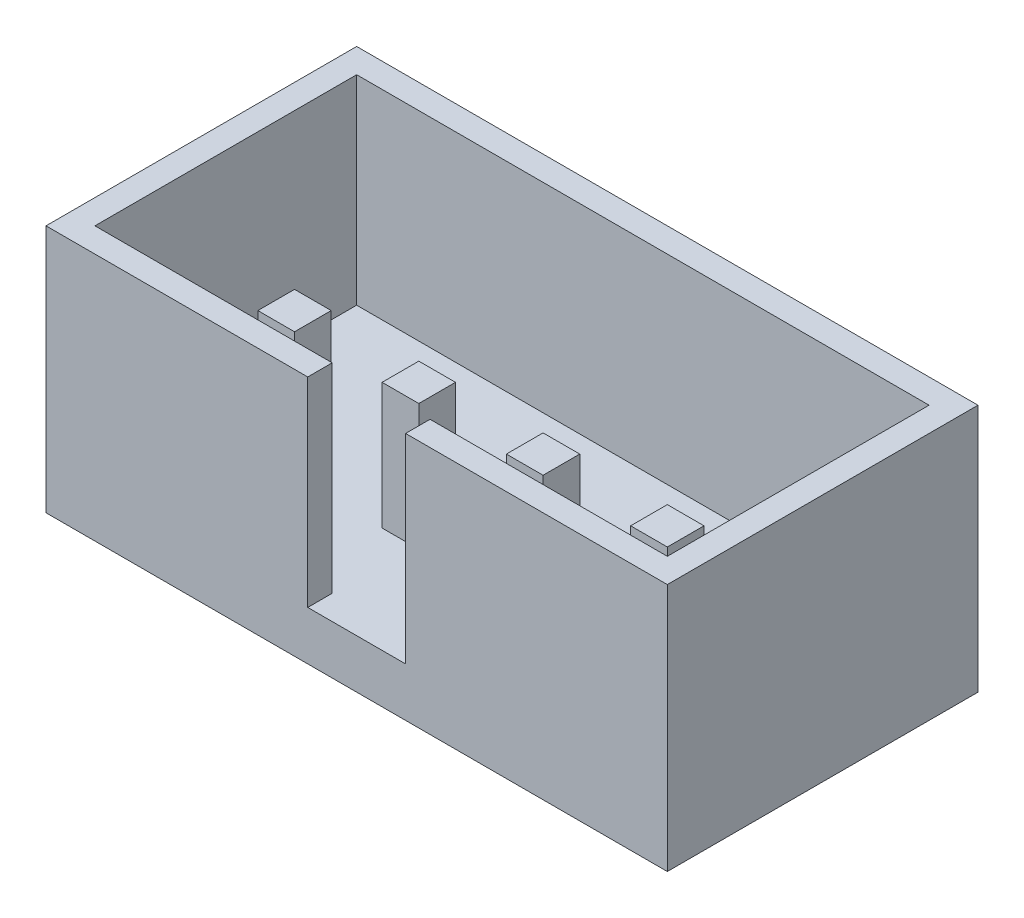
SolidWorks part; units mm, degrees
ref_plane "前视基准面" through (0, 0, 0) normal (0, 0, 1) x (1, 0, 0)
ref_plane "上视基准面" through (0, 0, 0) normal (0, 1, 0) x (1, 0, 0)
ref_plane "右视基准面" through (0, 0, 0) normal (1, 0, 0) x (0, 0, -1)
sketch "草图1" plane through (0, 0, 0) normal (0, 1, 0) x (1, 0, 0)
  line L0 (0, 7.1914) -> (0, -5.4429) construction
  line L1 (-6.35, 3.175) -> (6.35, 3.175)
  line L2 (-6.35, 3.175) -> (-6.35, -3.175)
  line L3 (-6.35, -3.175) -> (6.35, -3.175)
  line L4 (6.35, 3.175) -> (6.35, -3.175)
  line L5 (-10.6234, 0) -> (16.1963, 0) construction
  dimension "D1" = 12.7
  dimension "D2" = 6.35
extrude "拉伸1" add sketch "草图1" along normal blind 5.08
sketch "草图2" plane through (0, 5.08, 0) normal (0, 1, 0) x (-1, 0, 0)
  line L8 (5.85, -2.675) -> (5.85, 2.675)
  line L9 (5.85, 2.675) -> (-5.85, 2.675)
  line L10 (-5.85, 2.675) -> (-5.85, -2.675)
  line L11 (-5.85, -2.675) -> (5.85, -2.675)
  line L12 (5.85, -2.675) -> (5.85, 2.675)
  line L13 (5.85, 2.675) -> (-5.85, 2.675)
  line L14 (-5.85, 2.675) -> (-5.85, -2.675)
  line L15 (-5.85, -2.675) -> (5.85, -2.675)
  dimension "D1" = 0.5
extrude "切除-拉伸1" cut sketch "草图2" against normal offset from surface (4.08 mm away) 1 up to face at (0, 0, 0)
sketch "草图3" plane through (0, 0, 3.175) normal (0, 0, 1) x (1, 0, 0)
  line L0 (-6.35, 5.08) -> (6.35, 5.08) construction
  line L1 (-1, 5.08) -> (1, 5.08)
  line L2 (-1, 5.08) -> (-1, 1)
  line L3 (-1, 1) -> (1, 1)
  line L4 (1, 5.08) -> (1, 1)
  line L5 (5.85, 1) -> (-5.85, 1) construction
  line L6 (0, -1.5083) -> (0, 12.2426) construction
  dimension "D1" = 2
extrude "切除-拉伸2" cut sketch "草图3" against normal blind 1
sketch "草图4" plane through (0, 0, 0) normal (0, -1, 0) x (1, 0, 0)
  line L0 (7.6775, 0.635) -> (-8.5467, 0.635) construction
  line L1 (-6.35, 3.175) -> (6.35, 3.175) construction
  line L2 (0, -3.6953) -> (0, 4.0669) construction
  line L3 (-1.27, 2.1009) -> (-1.27, -0.7012) construction
  line L4 (-1.645, 1.01) -> (-0.895, 1.01)
  line L5 (-1.645, 1.01) -> (-1.645, 0.26)
  line L6 (-1.645, 0.26) -> (-0.895, 0.26)
  line L7 (-0.895, 1.01) -> (-0.895, 0.26)
  line L8 (0.895, 1.01) -> (1.645, 1.01)
  line L9 (0.895, 1.01) -> (0.895, 0.26)
  line L10 (0.895, 0.26) -> (1.645, 0.26)
  line L11 (1.645, 1.01) -> (1.645, 0.26)
  line L12 (3.435, 1.01) -> (4.185, 1.01)
  line L13 (3.435, 1.01) -> (3.435, 0.26)
  line L14 (3.435, 0.26) -> (4.185, 0.26)
  line L15 (4.185, 1.01) -> (4.185, 0.26)
  line L16 (-4.185, 1.01) -> (-3.435, 1.01)
  line L17 (-4.185, 1.01) -> (-4.185, 0.26)
  line L18 (-4.185, 0.26) -> (-3.435, 0.26)
  line L19 (-3.435, 1.01) -> (-3.435, 0.26)
  dimension "D1" = 2.54
  dimension "D2" = 0.75
  dimension "D3" = 0.75
  dimension "D4" = 1.27
extrude "拉伸2" add sketch "草图4" along normal blind 2 and the other way offset from surface (3.58 mm away) 1.5 other way up to face at (0, 5.08, 0.975)
